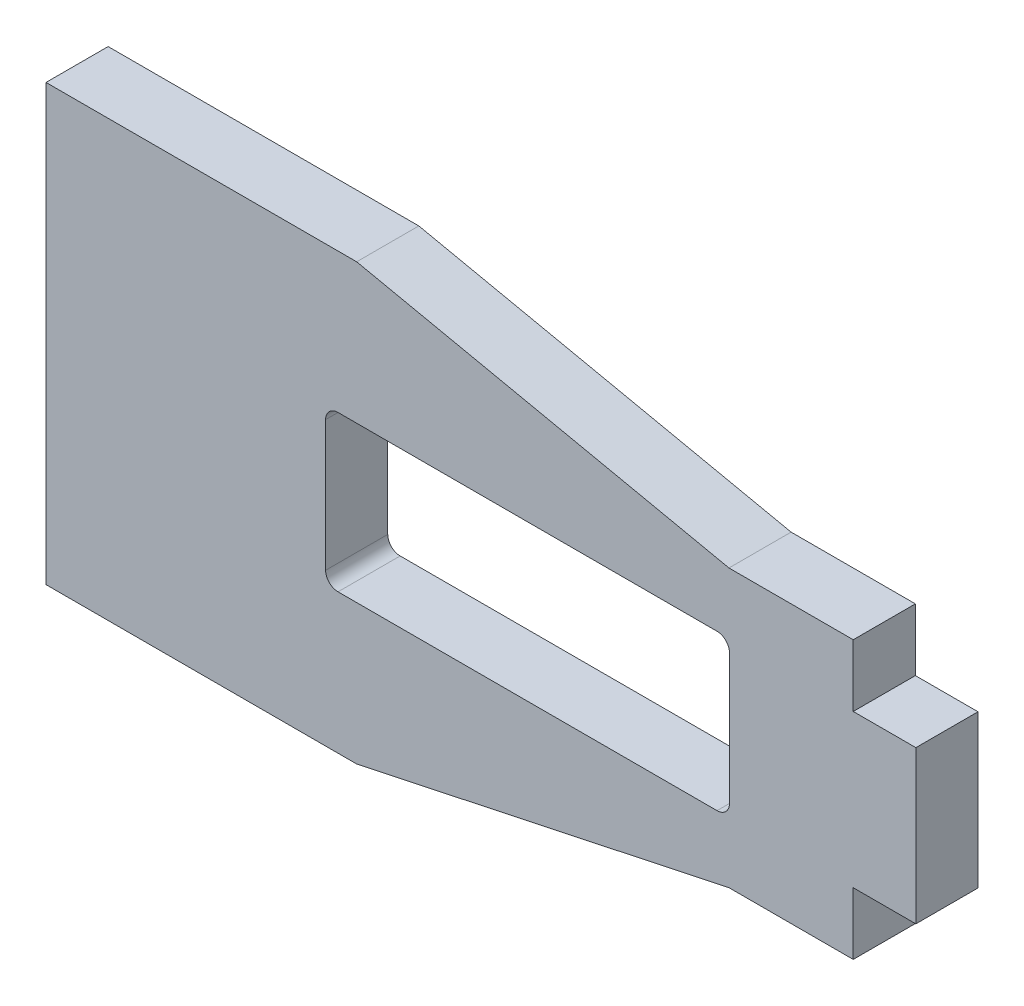
SolidWorks part; units mm, degrees
ref_plane "前视基准面" through (0, 0, 0) normal (0, 0, 1) x (1, 0, 0)
ref_plane "上视基准面" through (0, 0, 0) normal (0, 1, 0) x (1, 0, 0)
ref_plane "右视基准面" through (0, 0, 0) normal (1, 0, 0) x (0, 0, -1)
other "Configuration Table"
sketch "草图1" plane through (0, 0, 0) normal (0, 0, 1) x (1, 0, 0)
  line L0 (0, 0) -> (50000, 0) construction
  line L1 (0, 0) -> (0, 50000) construction
  line L3 (-70, 35) -> (70, 35)
  line L4 (-70, 35) -> (-70, -35)
  line L5 (-70, -35) -> (70, -35)
  line L6 (70, 35) -> (70, -35)
extrude "凸台-拉伸2" add sketch "草图1" along normal blind 10
sketch "草图2" plane through (0, 0, 10) normal (0, 0, 1) x (1, 0, 0)
  line L0 (0, 0) -> (50000, 0) construction
  line L1 (70, -35) -> (70, 35) construction
  line L2 (70, -12.282) -> (59.9203, -12.282)
  line L3 (70, -12.282) -> (70, 12.282)
  line L4 (70, 12.282) -> (59.9203, 12.282)
  line L5 (59.9203, -12.282) -> (59.9203, 12.282)
  line L6 (59.9203, 22.282) -> (70, 22.282)
  line L7 (59.9203, -12.282) -> (70, -12.282)
  line L8 (59.9203, -12.282) -> (59.9203, -22.282)
  line L9 (59.9203, -22.282) -> (70, -22.282)
  line L10 (70, -12.282) -> (70, -22.282)
  line L11 (70, 12.282) -> (70, 22.282)
  line L12 (59.9203, 12.282) -> (70, 12.282)
  line L13 (59.9203, 12.282) -> (59.9203, 22.282)
  line L14 (59.9203, -22.282) -> (39.9203, -22.282)
  line L15 (59.9203, 22.282) -> (39.9203, 22.282)
  line L16 (-70, -35) -> (70, -35) construction
  line L17 (-70, 35) -> (-20, 35)
  line L18 (-70, 35) -> (-70, -35)
  line L19 (-70, -35) -> (-20, -35)
  line L20 (-20, 35) -> (-20, -35)
  line L21 (-20, 35) -> (39.9203, 22.282)
  line L22 (39.9203, -22.282) -> (-20, -35)
  line L23 (-20, 35) -> (70, 35)
  line L24 (70, 35) -> (70, 22.282)
  line L25 (70, -22.282) -> (70, -35)
  line L26 (70, -35) -> (-20, -35)
  line L28 (-25, 12.5) -> (40, 12.5)
  line L29 (-25, 12.5) -> (-25, -12.5)
  line L30 (-25, -12.5) -> (40, -12.5)
  line L31 (40, 12.5) -> (40, -12.5)
  line M16 (-70, -35) -> (70, -35)
  line M17 (70, -35) -> (70, 35)
  line M18 (70, 35) -> (-70, 35)
  dimension "D1" = 30
  dimension "D2" = 25
extrude "切除-拉伸2" cut sketch "草图2" against normal blind 10 contours L29 L0 L20 L28 | L20 L0 L31 L28 | L0 L29 L30 L20 | L0 L20 L30 L31 | L21 L15 L6 M18 M17 | L13 L4 L6 M17 | L8 L9 L2 M17 | L14 L22 L9 M16 M17
fillet "圆角1" radius 2 4 edges at (-25, 12.5, 5) (40, 12.5, 5) (40, -12.5, 5) (-25, -12.5, 5)
